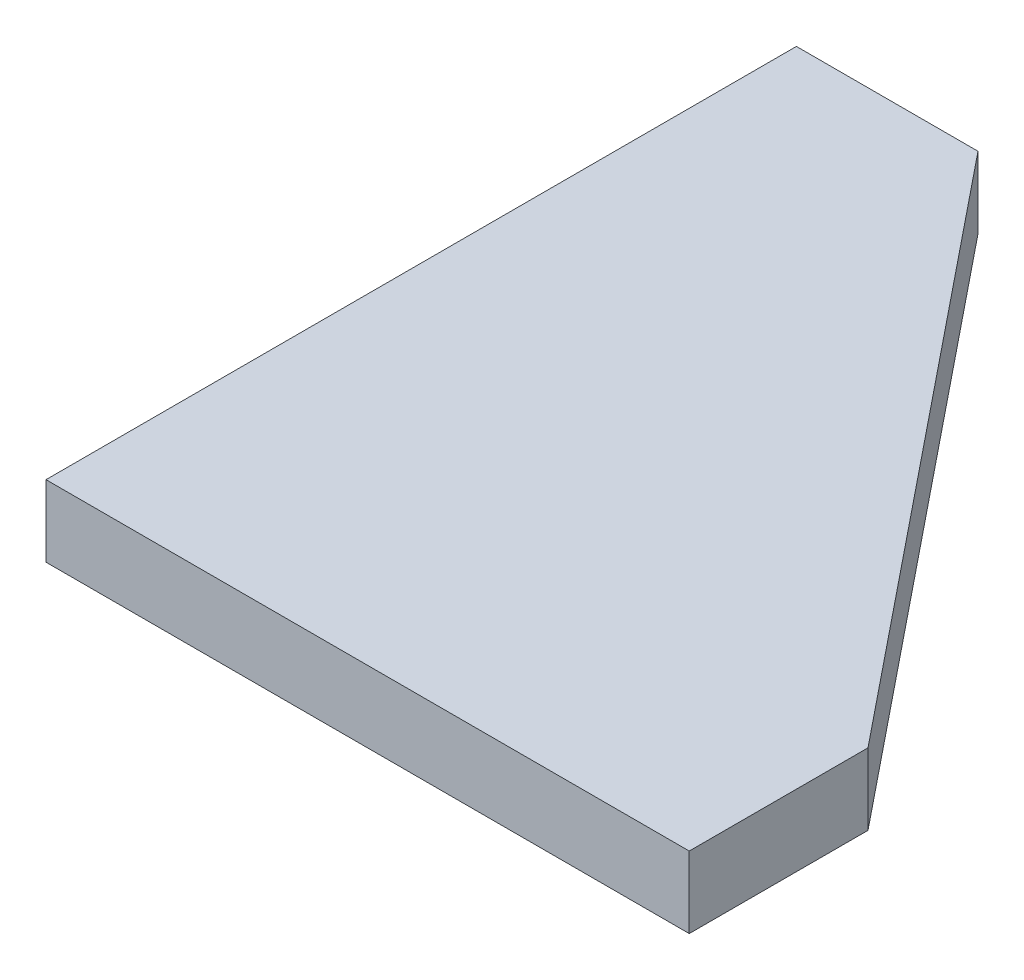
SolidWorks part; units mm, degrees
ref_plane "Спереди" through (0, 0, 0) normal (0, 0, 1) x (1, 0, 0)
ref_plane "Сверху" through (0, 0, 0) normal (0, 1, 0) x (1, 0, 0)
ref_plane "Справа" through (0, 0, 0) normal (1, 0, 0) x (0, 0, -1)
sketch "Эскиз1" plane through (0, 0, 0) normal (0, 1, 0) x (1, 0, 0)
  line L0 (10.1584, 41.98) -> (35.9839, 10)
  line L1 (0, 0) -> (35.9839, 0)
  line L2 (0, 0) -> (0, 41.98)
  line L3 (0, 41.98) -> (10.1584, 41.98)
  line L5 (210, 10) -> (0, 10) construction
  line L6 (35.9839, 10) -> (35.9839, 0)
extrude "Вытянуть1" add sketch "Эскиз1" along normal blind 4
